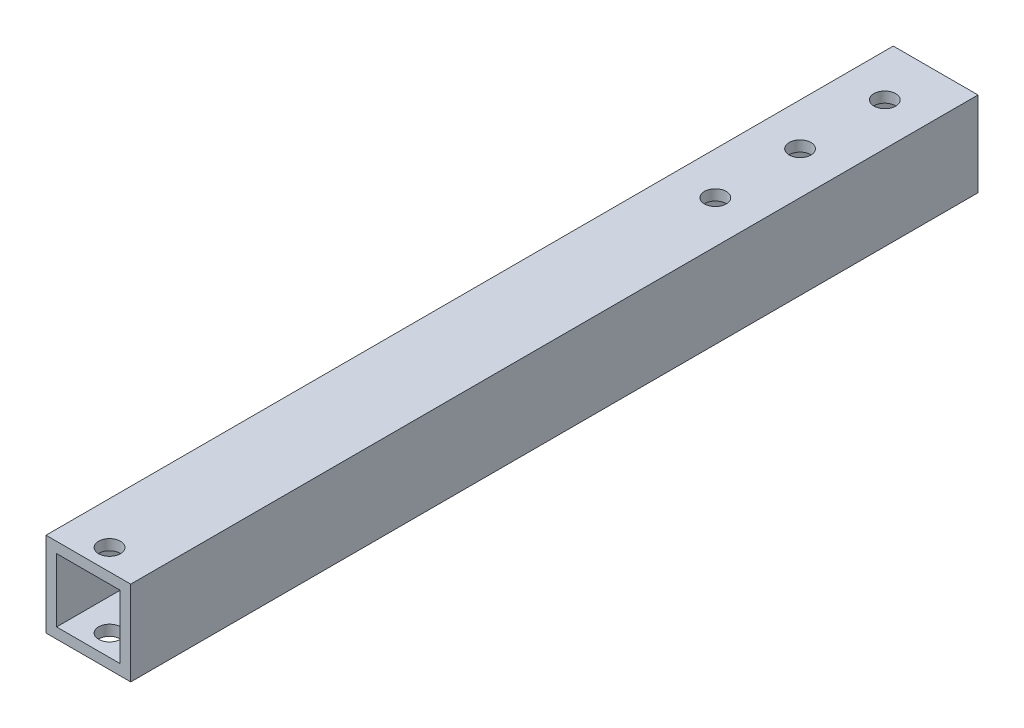
SolidWorks part; units mm, degrees
material "1060 Alloy"
ref_plane "Front Plane" through (0, 0, 0) normal (0, 0, 1) x (1, 0, 0)
ref_plane "Top Plane" through (0, 0, 0) normal (0, 1, 0) x (1, 0, 0)
ref_plane "Right Plane" through (0, 0, 0) normal (1, 0, 0) x (0, 0, -1)
sketch "Sketch2" plane through (0, 0, 0) normal (0, 0, 1) x (1, 0, 0)
  line L1 (12.7, -12.7) -> (-12.7, -12.7)
  line L2 (12.7, -12.7) -> (12.7, 12.7)
  line L3 (12.7, 12.7) -> (-12.7, 12.7)
  line L4 (-12.7, -12.7) -> (-12.7, 12.7)
  line L5 (12.7, -12.7) -> (-12.7, 12.7) construction
  line L6 (12.7, 12.7) -> (-12.7, -12.7) construction
  point P0 (0, 0)
  dimension "D1" = 25.4
extrude "Boss-Extrude1" add sketch "Sketch2" along normal blind 254 contours L4 L3 L2 L1
sketch "Sketch4" plane through (0, 0, 0) normal (0, 0, 1) x (1, 0, 0)
  line L0 (12.7, -12.7) -> (12.7, 12.7) construction
  line L1 (-9.525, -9.525) -> (9.525, -9.525)
  line L2 (-9.525, -9.525) -> (-9.525, 9.525)
  line L3 (-9.525, 9.525) -> (9.525, 9.525)
  line L4 (9.525, -9.525) -> (9.525, 9.525)
  line L5 (-9.525, -9.525) -> (9.525, 9.525) construction
  line L6 (-9.525, 9.525) -> (9.525, -9.525) construction
  line L7 (12.7, 12.7) -> (-12.7, 12.7) construction
  point P0 (0, 0)
  dimension "D1" = 3.175
  dimension "D2" = 3.175
extrude "Cut-Extrude1" cut sketch "Sketch4" along normal through all
sketch "Sketch5" plane through (0, 12.7, 0) normal (0, 1, 0) x (1, 0, 0)
  line L2 (12.7, 0) -> (-12.7, 0) construction
  circle A0 centre (0, -15.24) radius 3.2639
  point P4 (0, 0)
  dimension "D1" = 6.5278
  dimension "D2" = 15.24
extrude "Cut-Extrude2" cut sketch "Sketch5" against normal blind 304.8 contours A0
sketch "Sketch6" plane through (0, 12.7, 0) normal (0, 1, 0) x (1, 0, 0)
  line L0 (12.7, -254) -> (-12.7, -254) construction
  line L1 (12.7, 0) -> (-12.7, 0) construction
  circle A0 centre (0, -247.65) radius 3.2639
  point P4 (0, -254)
  dimension "D1" = 6.5278
  dimension "D2" = 247.65
extrude "Cut-Extrude3" cut sketch "Sketch6" against normal through all
sketch "Sketch8" plane through (0, 12.7, 0) normal (0, 1, 0) x (1, 0, 0)
  line L1 (12.7, 0) -> (-12.7, 0) construction
  circle A0 centre (0, -66.04) radius 3.2639
  circle A1 centre (0, -40.64) radius 3.2639
  point P9 (0, 0)
  dimension "D1" = 6.5278
  dimension "D2" = 40.64
  dimension "D3" = 66.04
extrude "Cut-Extrude4" cut sketch "Sketch8" against normal through all
